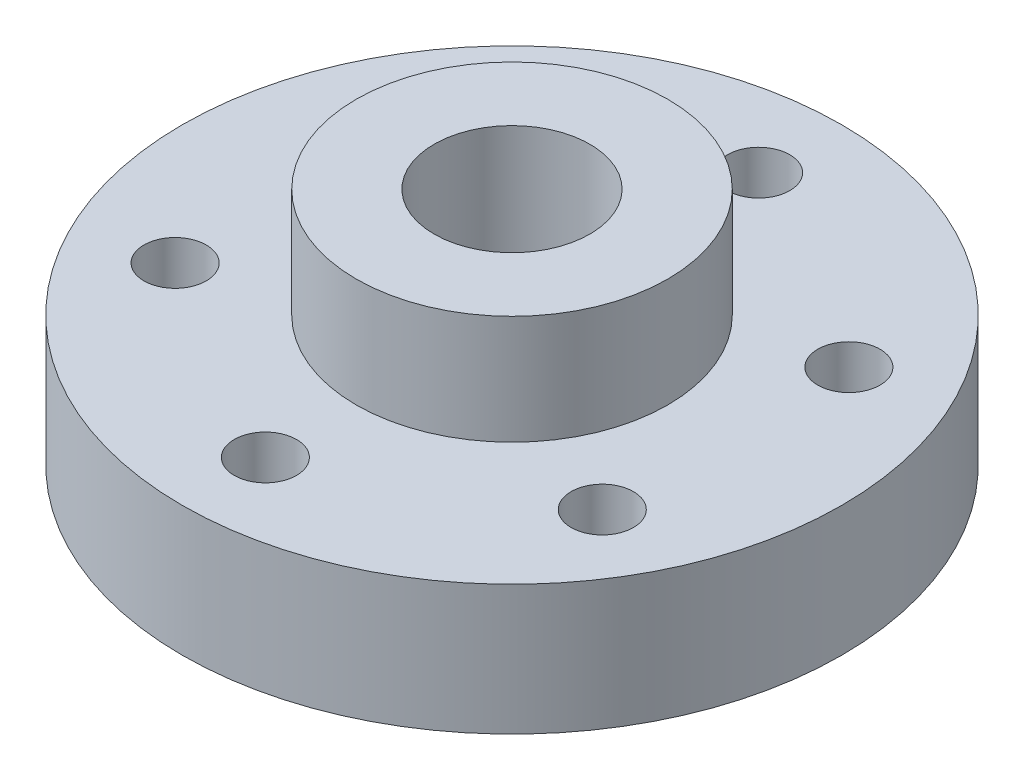
SolidWorks part; units mm, degrees
ref_plane "Front Plane" through (0, 0, 0) normal (0, 0, 1) x (1, 0, 0)
ref_plane "Top Plane" through (0, 0, 0) normal (0, 1, 0) x (1, 0, 0)
ref_plane "Right Plane" through (0, 0, 0) normal (1, 0, 0) x (0, 0, -1)
sketch "Sketch1" plane through (0, 0, 0) normal (0, 1, 0) x (1, 0, 0)
  circle A0 centre (0, 0) radius 3
  circle A1 centre (0, 0) radius 12.7
extrude "Boss-Extrude1" add sketch "Sketch1" along normal blind 5
sketch "Sketch2" plane through (0, 5, 0) normal (0, 1, 0) x (1, 0, 0)
  circle A0 centre (0, 0) radius 6
  circle A1 centre (0, 0) radius 3
extrude "Boss-Extrude2" add sketch "Sketch2" along normal blind 4.2
sketch "Sketch3" plane through (0, 5, 0) normal (0, 1, 0) x (1, 0, 0)
  circle A1 centre (0, 9.5) radius 1.2
  circle A2 centre (8.2272, 4.75) radius 1.2
  circle A3 centre (8.2272, -4.75) radius 1.2
  circle A4 centre (0, -9.5) radius 1.2
  circle A5 centre (-8.2272, -4.75) radius 1.2
  circle A6 centre (-8.2272, 4.75) radius 1.2
  point P18 (0, 0)
  dimension "D1" = 6
extrude "Cut-Extrude1" cut sketch "Sketch3" against normal through all
